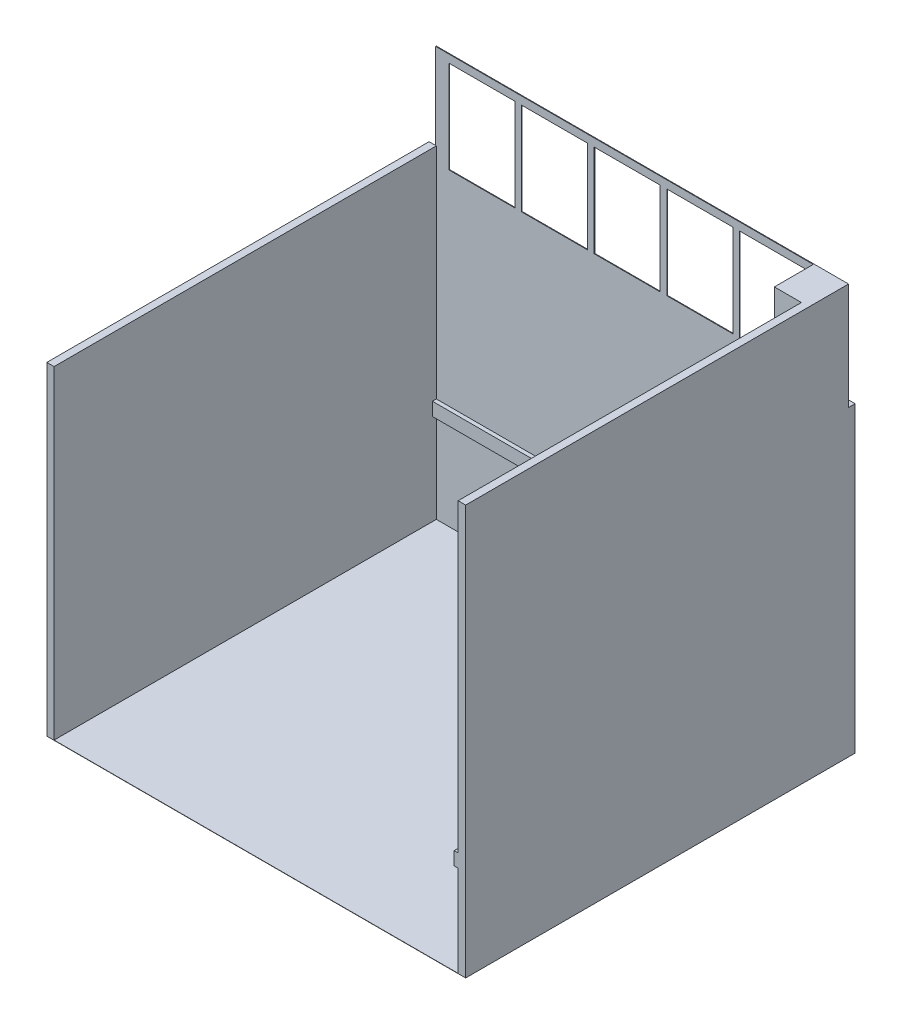
SolidWorks part; units mm, degrees
material "ABS"
ref_plane "Alzado" through (0, 0, 0) normal (0, 0, 1) x (1, 0, 0)
ref_plane "Planta" through (0, 0, 0) normal (0, 1, 0) x (1, 0, 0)
ref_plane "Vista lateral" through (0, 0, 0) normal (1, 0, 0) x (0, 0, -1)
sketch "Croquis1" plane through (0, 0, 0) normal (0, 1, 0) x (1, 0, 0)
  line L1 (-3029.5, 0) -> (40.5, 0)
  line L2 (-3029.5, 0) -> (-3029.5, -2900)
  line L3 (-3029.5, -2900) -> (40.5, -2900)
  line L4 (40.5, 0) -> (40.5, -2900)
  dimension "D1" = 3070
  dimension "D2" = 2900
extrude "Saliente-Extruir1" add sketch "Croquis1" along normal blind 2
sketch "Croquis4" plane through (0, 2, 0) normal (0, 1, 0) x (1, 0, 0)
  line L1 (40.5, 0) -> (-169.5, 0)
  line L2 (40.5, 0) -> (40.5, -300)
  line L3 (40.5, -300) -> (-169.5, -300)
  line L4 (-169.5, 0) -> (-169.5, -300)
  line L5 (40.5, -2900) -> (35.5, -2900)
  line L6 (40.5, -2900) -> (40.5, -300)
  line L7 (40.5, -300) -> (35.5, -300)
  line L8 (35.5, -2900) -> (35.5, -300)
  line L9 (-3029.5, 0) -> (-169.5, 0)
  line L10 (-3029.5, 0) -> (-3029.5, -5)
  line L11 (-3029.5, -5) -> (-169.5, -5)
  line L12 (-169.5, 0) -> (-169.5, -5)
  line M7 (-3029.5, 0) -> (-3029.5, -2900)
  line M8 (-3029.5, -2900) -> (40.5, -2900)
  line M9 (40.5, -2900) -> (40.5, 0)
  line M10 (40.5, 0) -> (-3029.5, 0)
  dimension "D1" = 210
  dimension "D2" = 300
  dimension "D3" = 5
  dimension "D4" = 5
extrude "Saliente-Extruir3" add sketch "Croquis4" along normal blind 3100 contours L8 L3 M8 M9 | L4 L3 M10 M9 | L11 L4 M7 M10
sketch "Croquis5" plane through (0, 2, 0) normal (0, 1, 0) x (1, 0, 0)
  line L0 (-3029.5, -2900) -> (35.5, -2900) construction
  line L1 (-3029.5, -5) -> (-3024.5, -5)
  line L2 (-3029.5, -5) -> (-3029.5, -2900)
  line L3 (-3029.5, -2900) -> (-3024.5, -2900)
  line L4 (-3024.5, -5) -> (-3024.5, -2900)
  dimension "D1" = 5
extrude "Saliente-Extruir4" add sketch "Croquis5" along normal blind 2450
sketch "Croquis6" plane through (0, 0, 5) normal (0, 0, 1) x (1, 0, 0)
  line L0 (-3024.5, 2452) -> (-3024.5, 2) construction
  line L1 (-3024.5, 792) -> (-169.5, 792)
  line L2 (-3024.5, 792) -> (-3024.5, 692)
  line L3 (-3024.5, 692) -> (-169.5, 692)
  line L4 (-169.5, 792) -> (-169.5, 692)
  line L5 (-169.5, 3102) -> (-169.5, 2) construction
  line L6 (-3024.5, 2) -> (35.5, 2) construction
  dimension "D1" = 100
  dimension "D2" = 790
extrude "Saliente-Extruir5" add sketch "Croquis6" along normal blind 30
sketch "Croquis7" plane through (-169.5, 0, 0) normal (-1, 0, 0) x (0, 0, 1)
  line L0 (0, 3102) -> (0, 0) construction
  line L1 (0, 792) -> (300, 792)
  line L2 (0, 792) -> (0, 692)
  line L3 (0, 692) -> (300, 692)
  line L4 (300, 792) -> (300, 692)
  line L5 (0, 0) -> (2900, 0) construction
  dimension "D1" = 300
  dimension "D2" = 100
  dimension "D3" = 792
extrude "Saliente-Extruir6" add sketch "Croquis7" along normal blind 30
sketch "Croquis8" plane through (0, 0, 300) normal (0, 0, 1) x (1, 0, 0)
  line L0 (35.5, 3102) -> (35.5, 2) construction
  line L1 (-199.5, 792) -> (35.5, 792)
  line L2 (-199.5, 792) -> (-199.5, 692)
  line L3 (-199.5, 692) -> (35.5, 692)
  line L4 (35.5, 792) -> (35.5, 692)
extrude "Saliente-Extruir7" add sketch "Croquis8" along normal blind 30
sketch "Croquis9" plane through (35.5, 0, 0) normal (-1, 0, 0) x (0, 0, 1)
  line L0 (2900, 2452) -> (2900, 0) construction
  line L1 (300, 792) -> (2900, 792)
  line L2 (300, 792) -> (300, 692)
  line L3 (300, 692) -> (2900, 692)
  line L4 (2900, 792) -> (2900, 692)
  line L5 (0, 0) -> (2900, 0) construction
  line L6 (300, 3102) -> (300, 792) construction
  dimension "D1" = 100
  dimension "D2" = 792
extrude "Saliente-Extruir8" add sketch "Croquis9" along normal blind 30
sketch "Croquis10" plane through (0, 0, 5) normal (0, 0, 1) x (1, 0, 0)
  line L0 (-3024.5, 2292) -> (-169.5, 2292) construction
  line L1 (-3024.5, 2452) -> (-3024.5, 792) construction
  line L2 (-169.5, 3102) -> (-169.5, 792) construction
  line L3 (-3024.5, 2) -> (-169.5, 2) construction
  dimension "D1" = 2290
sketch "Croquis11" plane through (0, 0, 5) normal (0, 0, 1) x (1, 0, 0)
  line L1 (-2928.9051, 3042) -> (-2428.9051, 3042)
  line L2 (-2928.9051, 3042) -> (-2928.9051, 2342)
  line L3 (-2928.9051, 2342) -> (-2428.9051, 2342)
  line L4 (-2428.9051, 3042) -> (-2428.9051, 2342)
  line L5 (-2378.9051, 2342) -> (-1878.9051, 2342)
  line L6 (-1878.9051, 3042) -> (-1878.9051, 2342)
  line L7 (-2378.9051, 3042) -> (-2378.9051, 2342)
  line L8 (-2378.9051, 3042) -> (-1878.9051, 3042)
  line L9 (-1828.9051, 2342) -> (-1328.9051, 2342)
  line L10 (-1328.9051, 3042) -> (-1328.9051, 2342)
  line L11 (-1828.9051, 3042) -> (-1828.9051, 2342)
  line L12 (-1828.9051, 3042) -> (-1328.9051, 3042)
  line L13 (-1278.9051, 2342) -> (-778.9051, 2342)
  line L14 (-778.9051, 3042) -> (-778.9051, 2342)
  line L15 (-1278.9051, 3042) -> (-1278.9051, 2342)
  line L16 (-1278.9051, 3042) -> (-778.9051, 3042)
  line L17 (-728.9051, 2342) -> (-228.9051, 2342)
  line L18 (-228.9051, 3042) -> (-228.9051, 2342)
  line L19 (-728.9051, 3042) -> (-728.9051, 2342)
  line L20 (-728.9051, 3042) -> (-228.9051, 3042)
  dimension "D1" = 5
extrude "Cortar-Extruir1" cut sketch "Croquis11" against normal blind 30
sketch "Croquis18" plane through (40.5, 0, 0) normal (1, 0, 0) x (0, 0, -1)
  line L1 (-2900, 3102) -> (0, 3102)
  line L2 (-2900, 3102) -> (-2900, 0)
  line L3 (-2900, 0) -> (0, 0)
  line L4 (0, 3102) -> (0, 0)
extrude "Saliente-Extruir9" add sketch "Croquis18" along normal blind 2
sketch "Croquis19" plane through (0, 2, 0) normal (0, 1, 0) x (1, 0, 0)
  line L0 (-2922.8859, -299.8273) -> (-2530.2192, -299.8273) construction
sketch "Croquis20" plane through (0, 0, 5) normal (0, 0, 1) x (1, 0, 0)
  line L0 (-2854.2177, 2042.3876) -> (-2214.2177, 2042.3876) construction
sketch "Croquis21" plane through (35.5, 0, 0) normal (-1, 0, 0) x (0, 0, 1)
  line L0 (2216.9361, 2731.9588) -> (2751.6028, 2731.9588) construction
sketch "Croquis22" plane through (-3024.5, 0, 0) normal (1, 0, 0) x (0, 0, -1)
  line L0 (-2738.2924, 2043.4096) -> (-2098.2924, 2043.4096) construction
sketch "Croquis23" plane through (42.5, 0, 0) normal (1, 0, 0) x (0, 0, -1)
  line L1 (-2900, 3102) -> (0, 3102)
  line L2 (-2900, 3102) -> (-2900, 0)
  line L3 (-2900, 0) -> (0, 0)
  line L4 (0, 3102) -> (0, 0)
extrude "Saliente-Extruir10" add sketch "Croquis23" along normal blind 50
sketch "Croquis24" plane through (0, 0, 0) normal (0, 0, -1) x (-1, 0, 0)
  line L1 (-92.5, 0) -> (3024.5, 0)
  line L2 (-92.5, 0) -> (-92.5, 2292)
  line L3 (-92.5, 2292) -> (3024.5, 2292)
  line L4 (3024.5, 0) -> (3024.5, 2292)
extrude "Saliente-Extruir11" add sketch "Croquis24" along normal blind 50
sketch "Croquis25" plane through (-3029.5, 0, 0) normal (-1, 0, 0) x (0, 0, 1)
  line L1 (2900, 0) -> (5, 0)
  line L2 (2900, 0) -> (2900, 2452)
  line L3 (2900, 2452) -> (5, 2452)
  line L4 (5, 0) -> (5, 2452)
extrude "Saliente-Extruir12" add sketch "Croquis25" along normal blind 50
